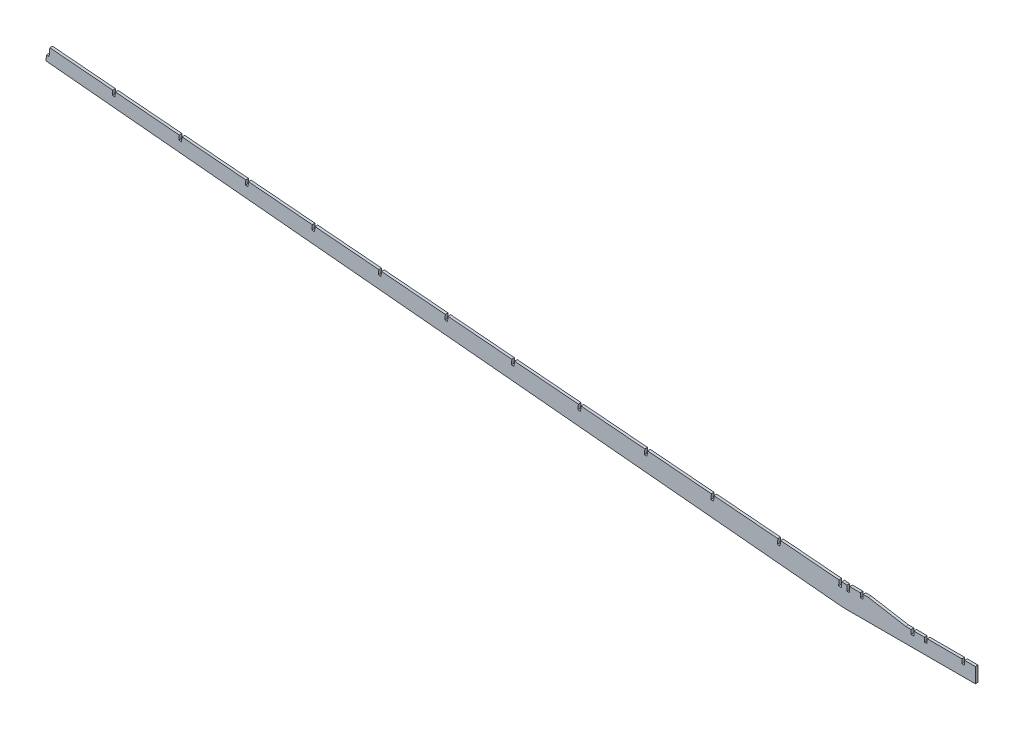
SolidWorks part; units mm, degrees
ref_plane "Front Plane" through (0, 0, 0) normal (0, 0, 1) x (1, 0, 0)
ref_plane "Top Plane" through (0, 0, 0) normal (0, 1, 0) x (1, 0, 0)
ref_plane "Right Plane" through (0, 0, 0) normal (1, 0, 0) x (0, 0, -1)
sketch "Sketch1" plane through (0, 0, 0) normal (0, 0, 1) x (1, 0, 0)
  line L0 (-951.0618, 63.2916) -> (-11.5367, -24.9026)
  line L8 (-8.3728, -25.1683) -> (-6.7788, -6.1851) construction
  line L9 (-6.7788, -6.1851) -> (-9.9426, -5.9194)
  line L10 (-9.9426, -5.9194) -> (-11.5367, -24.9026) construction
  line L11 (-11.5367, -24.9026) -> (-8.3728, -25.1683)
  line L12 (3.175, -25.5459) -> (3.175, -6.4959) construction
  line L13 (3.175, -6.4959) -> (0, -6.4959)
  line L14 (0, -6.4959) -> (0, -25.5459) construction
  line L15 (0, -25.5459) -> (3.175, -25.5459)
  line L17 (-943.9754, 109.7383) -> (-947.3666, 69.3536)
  line L19 (-8.3728, -25.1683) -> (0, -25.5459)
  line L20 (3.175, -25.5459) -> (152.4, -25.5459)
  line L21 (25.4, -0.1459) -> (69.85, -7.7659)
  line L22 (25.4, -0.1459) -> (-2.8123, -0.1459)
  line L23 (-2.8123, -0.1459) -> (-946.5481, 79.1019)
  line L24 (0, -6.4959) -> (0, -0.1459)
  line L25 (3.175, -6.4959) -> (3.175, -0.1459)
  line L26 (-6.7788, -6.1851) -> (-6.2474, 0.1426)
  line L27 (-9.9426, -5.9194) -> (-9.4113, 0.4083)
  line L28 (-9.9426, -5.9194) -> (-946.998, 73.7432)
  line L29 (69.85, -7.7659) -> (152.4, -7.7659)
  line L30 (152.4, -7.7659) -> (152.4, -25.5459)
  line L31 (76.2, -7.7659) -> (76.2, -25.5459)
  line L32 (79.375, -7.7659) -> (79.375, -25.5459)
  line L33 (76.2, -12.8459) -> (79.375, -12.8459)
  line L34 (15.875, -0.1459) -> (15.875, -5.2259)
  line L35 (15.875, -5.2259) -> (19.05, -5.2259)
  line L36 (19.05, -5.2259) -> (19.05, -0.1459)
  line L37 (92.075, -7.7659) -> (92.075, -12.8459)
  line L38 (92.075, -12.8459) -> (95.25, -12.8459)
  line L39 (95.25, -12.8459) -> (95.25, -7.7659)
  line L40 (136.525, -7.7659) -> (136.525, -12.8459)
  line L41 (136.525, -12.8459) -> (139.7, -12.8459)
  line L42 (139.7, -12.8459) -> (139.7, -7.7659)
  line L44 (-951.0618, 63.2916) -> (-950.5305, 69.6193)
  line L45 (-950.5305, 69.6193) -> (-947.3666, 69.3536)
  point P16 (0, 0)
  point P43 (0, 0)
  dimension "D1" = 25.4
  dimension "D2" = 6.35
extrude "Boss-Extrude1" add sketch "Sketch1" along normal blind 3.175
sketch "Sketch2" plane through (0, 0, 3.175) normal (0, 0, 1) x (1, 0, 0)
  line L1 (-73.9963, 64.5177) -> (-80.9723, -18.558)
  line L3 (-77.1601, 64.7834) -> (-84.1362, -18.2923)
  line L5 (-153.17, 68.7234) -> (-159.8855, -11.2491)
  line L7 (-232.3428, 72.9404) -> (-238.7996, -3.951)
  line L9 (-311.5203, 77.1018) -> (-317.7101, 3.3887)
  line L11 (-390.6978, 81.2631) -> (-396.6209, 10.7264)
  line L13 (-469.8812, 85.3537) -> (-475.5272, 18.1169)
  line L15 (-549.0652, 89.4374) -> (-554.4332, 25.5108)
  line L17 (-628.256, 93.4393) -> (-633.334, 32.9679)
  line L19 (-707.4489, 97.4177) -> (-712.2332, 40.4425)
  line L21 (-786.6506, 101.2897) -> (-791.1254, 48.0007)
  line L23 (-865.8569, 105.1088) -> (-870.014, 55.603)
  line L25 (-235.5067, 73.2061) -> (-241.9634, -3.6853)
  line L27 (-314.6841, 77.3675) -> (-320.874, 3.6544)
  line L29 (-393.8616, 81.5287) -> (-399.7848, 10.992)
  line L31 (-473.045, 85.6194) -> (-478.6911, 18.3826)
  line L33 (-552.229, 89.7031) -> (-557.5971, 25.7765)
  line L35 (-631.4199, 93.705) -> (-636.4978, 33.2336)
  line L37 (-710.6127, 97.6833) -> (-715.3971, 40.7082)
  line L39 (-789.8145, 101.5554) -> (-794.2893, 48.2664)
  line L41 (-9.9426, -5.9194) -> (-946.998, 73.7432)
  line L43 (-9.4113, 0.4083) -> (-946.5481, 79.1019)
  line L45 (-156.3339, 68.9891) -> (-163.0494, -10.9834)
  line L47 (-869.0207, 105.3745) -> (-873.1778, 55.8686)
  line M13 (-9.4113, 0.4083) -> (-946.5481, 79.1019)
extrude "Cut-Extrude1" cut sketch "Sketch2" against normal through all contours L47 L41 L23 M13 | L41 L21 L39 M13 | L41 L19 L37 M13 | L41 L17 L35 M13 | L41 L15 L33 M13 | L41 L13 L31 M13 | L41 L11 L29 M13 | L41 L9 L27 M13 | L41 L7 L25 M13 | L45 L41 L5 M13 | L41 L1 L3 M13
